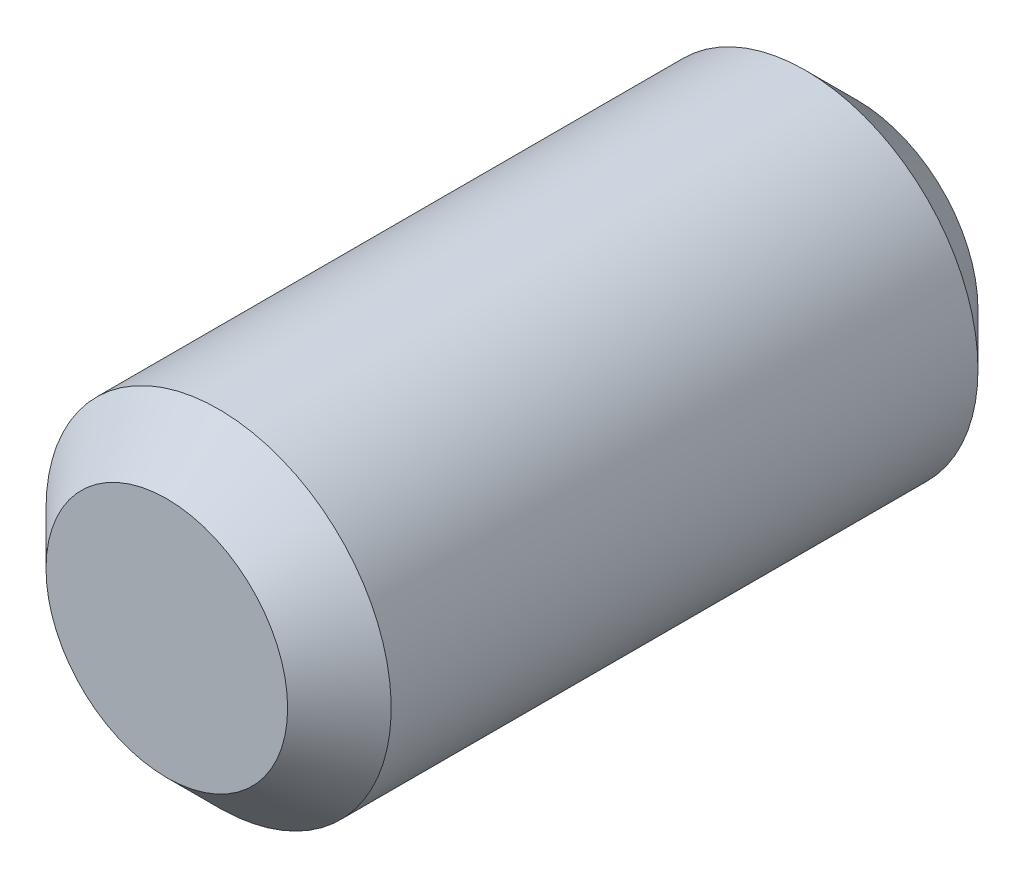
SolidWorks part; units mm, degrees
ref_plane "Ebene vorne" through (0, 0, 0) normal (0, 0, 1) x (1, 0, 0)
ref_plane "Ebene oben" through (0, 0, 0) normal (0, 1, 0) x (1, 0, 0)
ref_plane "Ebene rechts" through (0, 0, 0) normal (1, 0, 0) x (0, 0, -1)
sketch "Sketch2" plane through (0, 0, 0) normal (0, 0, 1) x (1, 0, 0)
  circle A0 centre (0, 0) radius 1
  dimension "D1" = 2
extrude "Boss-Extrude1" add sketch "Sketch2" along normal blind 4
chamfer "Chamfer1" distance 0.3 angle 45 2 edges at (1, 0, 0) (1, 0, 4)
